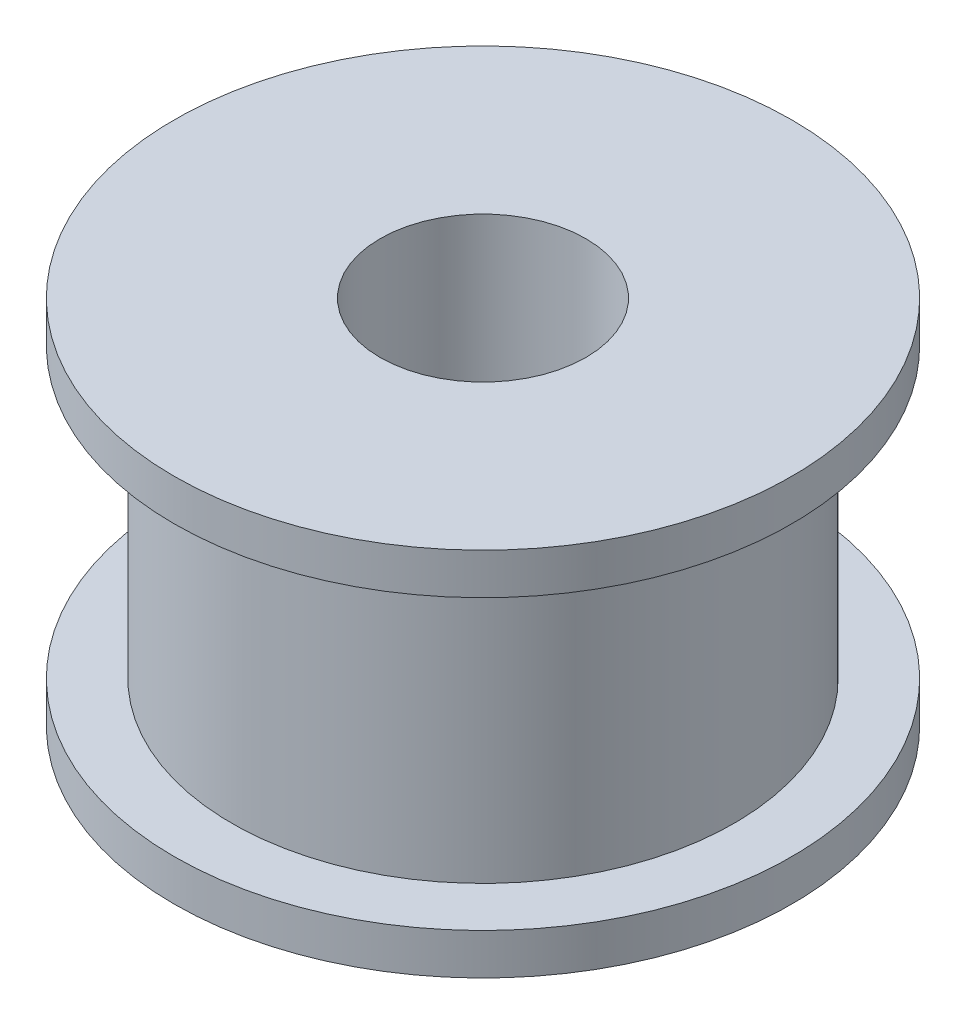
SolidWorks part; units mm, degrees
material "Chrome Stainless Steel"
ref_plane "Front Plane" through (0, 0, 0) normal (0, 0, 1) x (1, 0, 0)
ref_plane "Top Plane" through (0, 0, 0) normal (0, 1, 0) x (1, 0, 0)
ref_plane "Right Plane" through (0, 0, 0) normal (1, 0, 0) x (0, 0, -1)
sketch "Sketch1" plane through (0, 0, 0) normal (0, 0, 1) x (1, 0, 0)
  line L0 (0, 0) -> (7.5, 0)
  line L1 (7.5, 0) -> (7.5, -1)
  line L2 (7.5, -1) -> (6.1, -1)
  line L3 (6.1, -1) -> (6.1, -8)
  line L4 (6.1, -8) -> (7.5, -8)
  line L5 (7.5, -8) -> (7.5, -9)
  line L6 (7.5, -9) -> (0, -9)
  line L7 (0, -9) -> (0, 0)
  line L8 (0, 3.04) -> (0, 6.4) construction
  dimension "D1" = 9
  dimension "D2" = 7
  dimension "D3" = 6.1
  dimension "D4" = 7.5
revolve "Revolve1" add sketch "Sketch1" angle 360 about L8
sketch "Sketch2" plane through (0, 0, 0) normal (0, 1, 0) x (1, 0, 0)
  circle A0 centre (0, 0) radius 2.5
  dimension "D1" = 5
extrude "Cut-Extrude1" cut sketch "Sketch2" against normal blind 10
